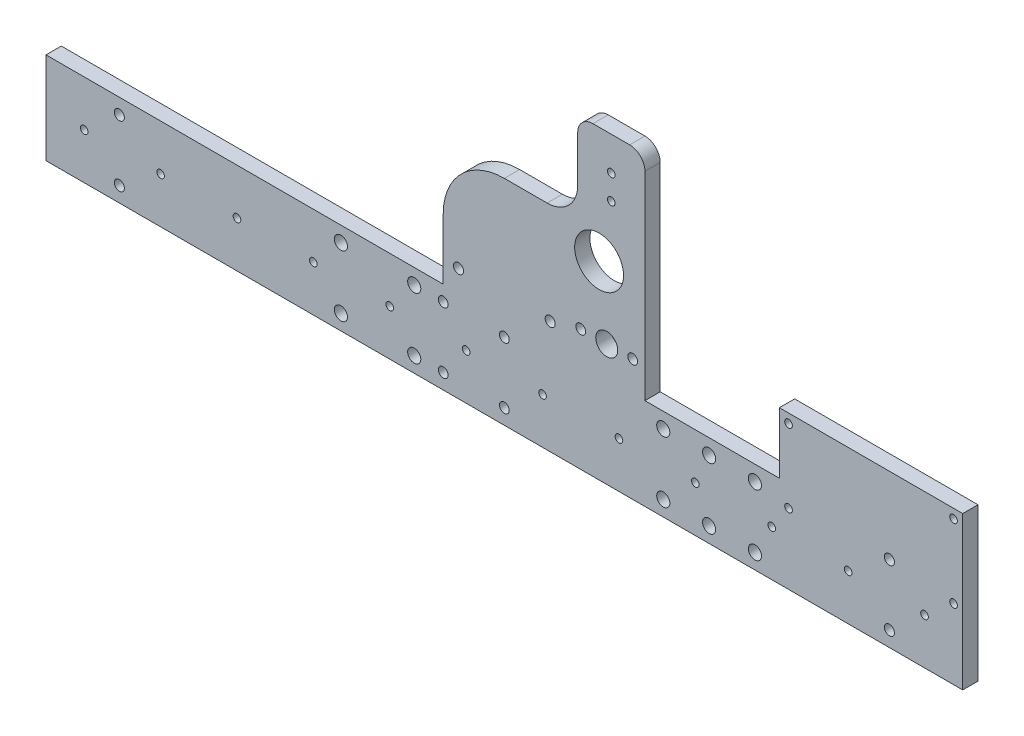
SolidWorks part; units mm, degrees
material "5052-O"
ref_plane "前基準面" through (0, 0, 0) normal (0, 0, 1) x (1, 0, 0)
ref_plane "上基準面" through (0, 0, 0) normal (0, 1, 0) x (1, 0, 0)
ref_plane "右基準面" through (0, 0, 0) normal (1, 0, 0) x (0, 0, -1)
sketch "草圖1" plane through (0, 0, 0) normal (0, 0, 1) x (1, 0, 0)
  line L1 (-150, -15) -> (150, -15)
  line L2 (-150, -15) -> (-150, 15)
  line L3 (-150, 15) -> (150, 15)
  line L4 (150, -15) -> (150, 15)
  line L5 (-150, -15) -> (150, 15) construction
  line L6 (-150, 15) -> (150, -15) construction
  point P0 (0, 0)
  dimension "D1" = 300
  dimension "D2" = 30
extrude "填料-伸長1" add sketch "草圖1" along normal blind 5
hole_wizard "M3 餘隙孔1" positions "草圖7" profile "草圖8" hole size "M3" standard "Ansi Metric" end condition through all
sketch "草圖7" plane through (0, 0, 5) normal (0, 0, 1) x (1, 0, 0)
  line L0 (0, 0) -> (-10, 0) construction
  line L4 (-20, -10) -> (0, -10) construction
  line L5 (-20, -10) -> (-20, 10) construction
  line L6 (-20, 10) -> (0, 10) construction
  line L7 (0, -10) -> (0, 10) construction
  line L8 (-20, -10) -> (0, 10) construction
  line L9 (-20, 10) -> (0, -10) construction
  point P9 (0, 10)
  point P60 (-20, -10)
  point P61 (-20, 10)
  point P62 (0, -10)
  dimension "D1" = 10
  dimension "D2" = 20
  dimension "D3" = 20
sketch "草圖8" plane through (0, -10, 5) normal (1, 0, 0) x (0, -1, 0)
  line L0 (0, 0) -> (0, 5)
  line L1 (0, 5) -> (1.6, 5)
  line L2 (1.6, 5) -> (1.6, 0)
  line L5 (1.6, 0) -> (0, 0)
  line L11 (0, -6.35) -> (0, 107.95) construction
  dimension "貫穿孔直徑" = 3.2
  dimension "貫穿孔深度" = 5
hole_wizard "M3x0.5 螺紋孔1" positions "草圖3" profile "草圖4" tap size "M3x0.5" standard "Ansi Metric" end condition through all
sketch "草圖3" plane through (0, 0, 5) normal (0, 0, 1) x (1, 0, 0)
  line L0 (-12.5, 0) -> (12.5, 0) construction
  point P0 (-12.5, 0)
  dimension "D1" = 25
sketch "草圖4" plane through (-12.5, 0, 5) normal (1, 0, 0) x (0, -1, 0)
  line L0 (0, 0) -> (0, 5)
  line L1 (0, 5) -> (1.25, 5)
  line L2 (1.25, 5) -> (1.25, 0)
  line L5 (1.25, 0) -> (0, 0)
  line L11 (0, -6.35) -> (0, 107.95) construction
  dimension "貫穿螺孔鑽直徑" = 2.5
  dimension "貫穿螺孔鑽深度" = 5
hole_wizard "M4 餘隙孔2" positions "草圖9" profile "草圖10" hole size "M4" standard "Ansi Metric" end condition through all
sketch "草圖9" plane through (0, 0, 5) normal (0, 0, 1) x (1, 0, 0)
  line L2 (52, -10) -> (52, 10) construction
  line L8 (-150, -15) -> (150, -15) construction
  point P55 (52, -10)
  point P56 (52, 10)
  dimension "D1" = 5
  dimension "D2" = 20
  dimension "D3" = 52
sketch "草圖10" plane through (52, -10, 5) normal (1, 0, 0) x (0, -1, 0)
  line L0 (0, 0) -> (0, 5)
  line L1 (0, 5) -> (2.15, 5)
  line L2 (2.15, 5) -> (2.15, 0)
  line L5 (2.15, 0) -> (0, 0)
  line L11 (0, -6.35) -> (0, 107.95) construction
  dimension "貫穿孔直徑" = 4.3
  dimension "貫穿孔深度" = 5
hole_wizard "M4x0.7 螺紋孔2" positions "草圖11" profile "草圖12" tap size "M4x0.7" standard "Ansi Metric" end condition through all
sketch "草圖11" plane through (0, 0, 5) normal (0, 0, 1) x (1, 0, 0)
  line L0 (-150, 0) -> (-126, 0) construction
  line L1 (-150, 15) -> (-150, -15) construction
  line L4 (-126, -10) -> (-126, 10) construction
  point P9 (-126, -10)
  point P10 (-126, 10)
  dimension "D1" = 20
  dimension "D2" = 24
sketch "草圖12" plane through (-126, 10, 5) normal (1, 0, 0) x (0, -1, 0)
  line L0 (0, 0) -> (0, 5)
  line L1 (0, 5) -> (1.65, 5)
  line L2 (1.65, 5) -> (1.65, 0)
  line L5 (1.65, 0) -> (0, 0)
  line L11 (0, -6.35) -> (0, 107.95) construction
  dimension "貫穿螺孔鑽直徑" = 3.3
  dimension "貫穿螺孔鑽深度" = 5
pattern_linear "直線複製排列1" count 6 spacing 25 along (-1, 0, 0) count 7 spacing 25 along (1, 0, 0) of "M3x0.5 螺紋孔1"
mirror "鏡射1" about plane through (0, 0, 0) normal (1, 0, 0) of "M4x0.7 螺紋孔2"
sketch "草圖16" plane through (0, 0, 0) normal (0, 0, 1) x (1, 0, 0)
  line L0 (-20, 15) -> (46, 15)
  line L1 (150, 15) -> (-150, 15) construction
  line L4 (-20, 35) -> (-20, 15)
  line L5 (0, 0) -> (0, 55) construction
  line L9 (46, 15) -> (46, 55)
  line L10 (46, 55) -> (0, 55)
  arc A1 (-20, 35) -> (0, 55) centre (0, 35) cw
  dimension "D1" = 20
  dimension "D2" = 55
  dimension "D4" = 46
extrude "填料-伸長3" add sketch "草圖16" along normal through all
sketch "草圖13" plane through (0, 0, 0) normal (0, 0, 1) x (1, 0, 0)
  circle A1 centre (33.5, 24.8) radius 3.6
  dimension "D2" = 7.2
  dimension "D3" = 24.8
  dimension "D4" = 33.5
extrude "除料-伸長2" cut sketch "草圖13" along normal through all
hole_wizard "M4x0.7 螺紋孔3" positions "草圖19" profile "草圖20" tap size "M4x0.7" standard "Ansi Metric" end condition through all
sketch "草圖19" plane through (0, 0, 5) normal (0, 0, 1) x (1, 0, 0)
  line L0 (0, 57.0101) -> (0, 22) construction
  line L4 (-15, 22) -> (15, 22) construction
  point P9 (-15, 22)
  point P10 (15, 22)
  dimension "D1" = 30
  dimension "D2" = 22
  dimension "D3" = 0
sketch "草圖20" plane through (15, 22, 5) normal (1, 0, 0) x (0, -1, 0)
  line L0 (0, 0) -> (0, 5)
  line L1 (0, 5) -> (1.65, 5)
  line L2 (1.65, 5) -> (1.65, 0)
  line L5 (1.65, 0) -> (0, 0)
  line L11 (0, -6.35) -> (0, 107.95) construction
  dimension "貫穿螺孔鑽直徑" = 3.3
  dimension "貫穿螺孔鑽深度" = 5
hole_wizard "M4 餘隙孔1" positions "草圖21" profile "草圖22" hole size "M4" standard "Ansi Metric" end condition through all
sketch "草圖21" plane through (0, 0, 5) normal (0, 0, 1) x (1, 0, 0)
  line L0 (0, 0) -> (-41.5, 0) construction
  line L4 (-53.5, -10) -> (-29.5, -10) construction
  line L5 (-53.5, -10) -> (-53.5, 10) construction
  line L6 (-53.5, 10) -> (-29.5, 10) construction
  line L7 (-29.5, -10) -> (-29.5, 10) construction
  line L8 (-53.5, -10) -> (-29.5, 10) construction
  line L9 (-53.5, 10) -> (-29.5, -10) construction
  point P11 (-29.5, 10)
  point P60 (-53.5, -10)
  point P61 (-53.5, 10)
  point P62 (-29.5, -10)
  dimension "D1" = 41.5
  dimension "D2" = 24
  dimension "D3" = 20
sketch "草圖22" plane through (-29.5, -10, 5) normal (1, 0, 0) x (0, -1, 0)
  line L0 (0, 0) -> (0, 5)
  line L1 (0, 5) -> (2.15, 5)
  line L2 (2.15, 5) -> (2.15, 0)
  line L5 (2.15, 0) -> (0, 0)
  line L11 (0, -6.35) -> (0, 107.95) construction
  dimension "貫穿孔直徑" = 4.3
  dimension "貫穿孔深度" = 5
sketch "草圖26" plane through (0, 55, 0) normal (0, 1, 0) x (1, 0, 0)
  line L0 (46, -5) -> (0, -5) construction
  line L1 (46, 0) -> (24, 0)
  line L2 (46, 0) -> (46, -5)
  line L3 (46, -5) -> (24, -5)
  line L4 (24, 0) -> (24, -5)
  line L5 (46, 0) -> (0, 0) construction
  line L7 (46, -5) -> (46, 0) construction
  point P9 (46, -2.5)
  dimension "D1" = 22
extrude "填料-伸長4" add sketch "草圖26" along normal blind 30
hole_wizard "M3x0.5 螺紋孔2" positions "草圖23" profile "草圖24" tap size "M3x0.5" standard "Ansi Metric" end condition through all
sketch "草圖23" plane through (0, 0, 5) normal (0, 0, 1) x (1, 0, 0)
  line L0 (35, 74) -> (35, 66) construction
  line L3 (46, 15) -> (46, 85) construction
  line L5 (24, 85) -> (46, 85) construction
  point P0 (35, 74)
  point P1 (35, 66)
  dimension "D1" = 11
  dimension "D2" = 8
  dimension "D3" = 11
sketch "草圖24" plane through (35, 74, 5) normal (1, 0, 0) x (0, -1, 0)
  line L0 (0, 0) -> (0, 5)
  line L1 (0, 5) -> (1.25, 5)
  line L2 (1.25, 5) -> (1.25, 0)
  line L5 (1.25, 0) -> (0, 0)
  line L11 (0, -6.35) -> (0, 107.95) construction
  dimension "貫穿螺孔鑽直徑" = 2.5
  dimension "貫穿螺孔鑽深度" = 5
hole_wizard "M3 餘隙孔2" positions "草圖31" profile "草圖32" hole size "M3" standard "Ansi Metric" end condition through all
sketch "草圖31" plane through (0, 0, 5) normal (0, 0, 1) x (1, 0, 0)
  line L12 (33.5, 24.8) -> (42, 24.8) construction
  point P32 (42, 24.8)
  point P38 (25, 24.8)
  dimension "D2" = 17
  dimension "D1" = 8.5
sketch "草圖32" plane through (25, 24.8, 5) normal (1, 0, 0) x (0, -1, 0)
  line L0 (0, 0) -> (0, 5)
  line L1 (0, 5) -> (1.6, 5)
  line L2 (1.6, 5) -> (1.6, 0)
  line L5 (1.6, 0) -> (0, 0)
  line L11 (0, -6.35) -> (0, 107.95) construction
  dimension "貫穿孔直徑" = 3.2
  dimension "貫穿孔深度" = 5
fillet "圓角2" radius 5 2 edges at (46, 85, 2.5) (24, 85, 2.5)
sketch "草圖36" plane through (0, 0, 5) normal (0, 0, 1) x (1, 0, 0)
  line L0 (46, 15) -> (46, 80) construction
  line L1 (29, 85) -> (41, 85) construction
  circle A0 centre (31, 47) radius 8
  dimension "D1" = 16
  dimension "D2" = 15
  dimension "D3" = 38
extrude "除料-伸長3" cut sketch "草圖36" against normal through all
pattern_linear "直線複製排列3" count 3 spacing 15 along (1, 0, 0) of "M4 餘隙孔2"
sketch "草圖40" plane through (0, 15, 0) normal (0, 1, 0) x (1, 0, 0)
  line L1 (150, 0) -> (90, 0)
  line L2 (150, 0) -> (150, -5)
  line L3 (150, -5) -> (90, -5)
  line L4 (90, 0) -> (90, -5)
  line L5 (64.85, -5) -> (69.15, -5) construction
  dimension "D1" = 60
extrude "填料-伸長6" add sketch "草圖40" along normal blind 20
hole_wizard "M3x0.5 螺紋孔3" positions "草圖42" profile "草圖43" tap size "M3x0.5" standard "Ansi Metric" end condition through all
sketch "草圖42" plane through (0, 0, 0) normal (0, 0, -1) x (-1, 0, 0)
  line L1 (-147, 32) -> (-93, 32) construction
  line L2 (-147, 32) -> (-147, 8) construction
  line L3 (-147, 8) -> (-93, 8) construction
  line L4 (-93, 32) -> (-93, 8) construction
  line L5 (-150, 35) -> (-90, 35) construction
  line L6 (-150, -15) -> (-150, 35) construction
  point P0 (-147, 32)
  point P1 (-93, 8)
  point P96 (-147, 8)
  point P97 (-93, 32)
  dimension "D1" = 24
  dimension "D2" = 54
  dimension "D3" = 3
  dimension "D4" = 3
sketch "草圖43" plane through (147, 32, 0) normal (1, 0, 0) x (0, 1, 0)
  line L0 (0, 0) -> (0, 5)
  line L1 (0, 5) -> (1.25, 5)
  line L2 (1.25, 5) -> (1.25, 0)
  line L5 (1.25, 0) -> (0, 0)
  line L11 (0, -6.35) -> (0, 107.95) construction
  dimension "貫穿螺孔鑽直徑" = 2.5
  dimension "貫穿螺孔鑽深度" = 5
fillet "圓角3" radius 10 1 edges at (24, 55, 2.5)
